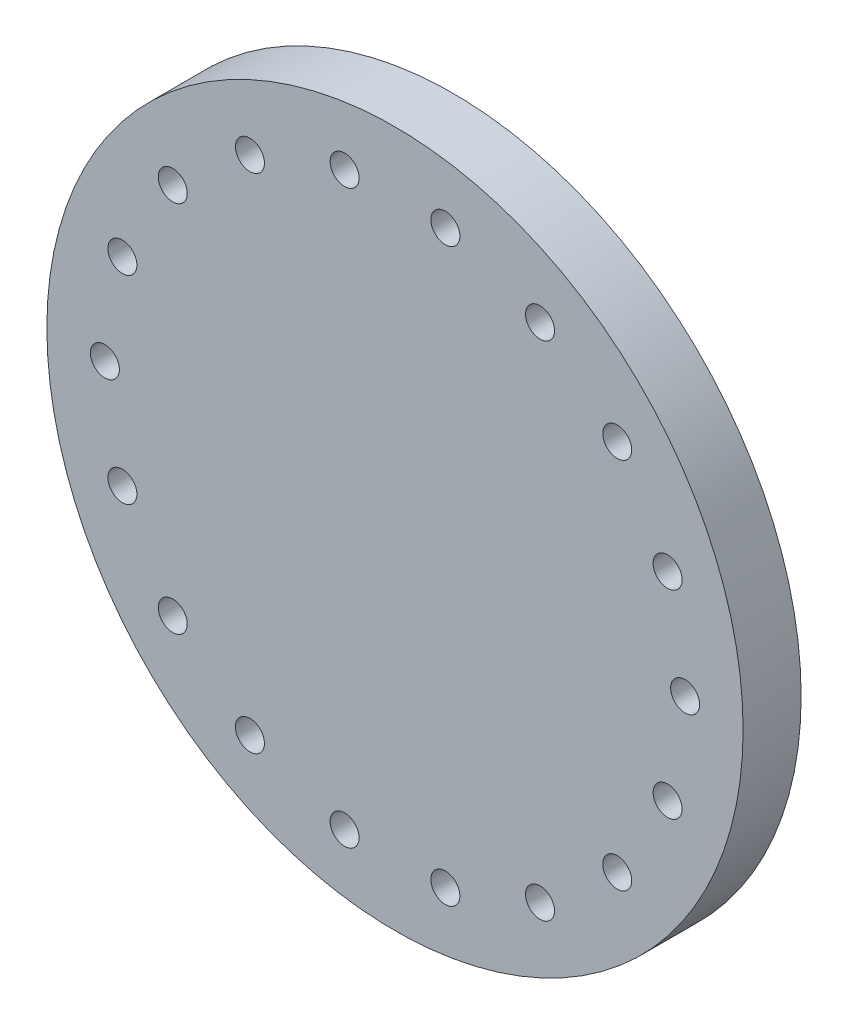
SolidWorks part; units mm, degrees
ref_plane "Front Plane" through (0, 0, 0) normal (0, 0, 1) x (1, 0, 0)
ref_plane "Top Plane" through (0, 0, 0) normal (0, 1, 0) x (1, 0, 0)
ref_plane "Right Plane" through (0, 0, 0) normal (1, 0, 0) x (0, 0, -1)
sketch "Sketch1" plane through (0, 0, 0) normal (0, 0, 1) x (1, 0, 0)
  circle A0 centre (0, 0) radius 76.2
  circle A1 centre (-63.5, 0) radius 3.175
  circle A2 centre (-59.6705, 21.7183) radius 3.175
  circle A3 centre (-48.6438, 40.817) radius 3.175
  circle A4 centre (-31.75, 54.9926) radius 3.175
  circle A5 centre (-11.0267, 62.5353) radius 3.175
  circle A6 centre (11.0267, 62.5353) radius 3.175
  circle A7 centre (31.75, 54.9926) radius 3.175
  circle A8 centre (48.6438, 40.817) radius 3.175
  circle A9 centre (59.6705, 21.7183) radius 3.175
  circle A10 centre (63.5, 0) radius 3.175
  circle A11 centre (59.6705, -21.7183) radius 3.175
  circle A12 centre (48.6438, -40.817) radius 3.175
  circle A13 centre (31.75, -54.9926) radius 3.175
  circle A14 centre (11.0267, -62.5353) radius 3.175
  circle A15 centre (-11.0267, -62.5353) radius 3.175
  circle A16 centre (-31.75, -54.9926) radius 3.175
  circle A17 centre (-48.6438, -40.817) radius 3.175
  circle A18 centre (-59.6705, -21.7183) radius 3.175
  point P42 (0, 0)
  dimension "D1" = 63.5
  dimension "D2" = 18
extrude "Boss-Extrude1" add sketch "Sketch1" along normal blind 12.7
